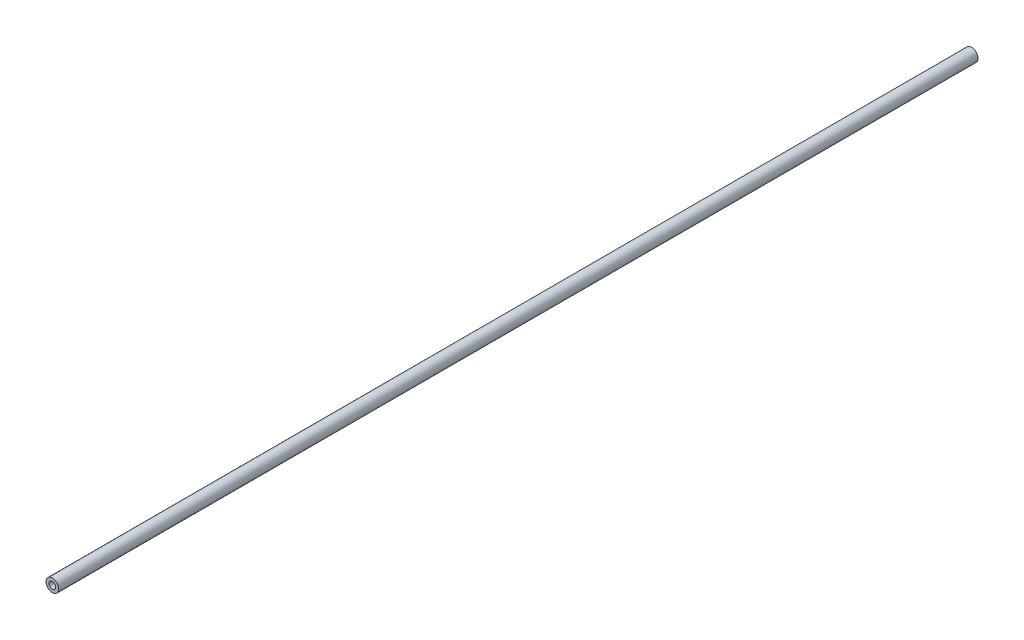
SolidWorks part; units mm, degrees
material "6061-T6 (SS)"
ref_plane "Front Plane" through (0, 0, 0) normal (0, 0, 1) x (1, 0, 0)
ref_plane "Top Plane" through (0, 0, 0) normal (0, 1, 0) x (1, 0, 0)
ref_plane "Right Plane" through (0, 0, 0) normal (1, 0, 0) x (0, 0, -1)
sketch "Sketch1" plane through (0, 0, 0) normal (0, 0, 1) x (1, 0, 0)
  circle A0 centre (0, 0) radius 4.7625
  circle A1 centre (0, 0) radius 2.4892
  dimension "D1" = 9.525
  dimension "D2" = 4.9784
extrude "Boss-Extrude1" add sketch "Sketch1" against normal blind 685.8
